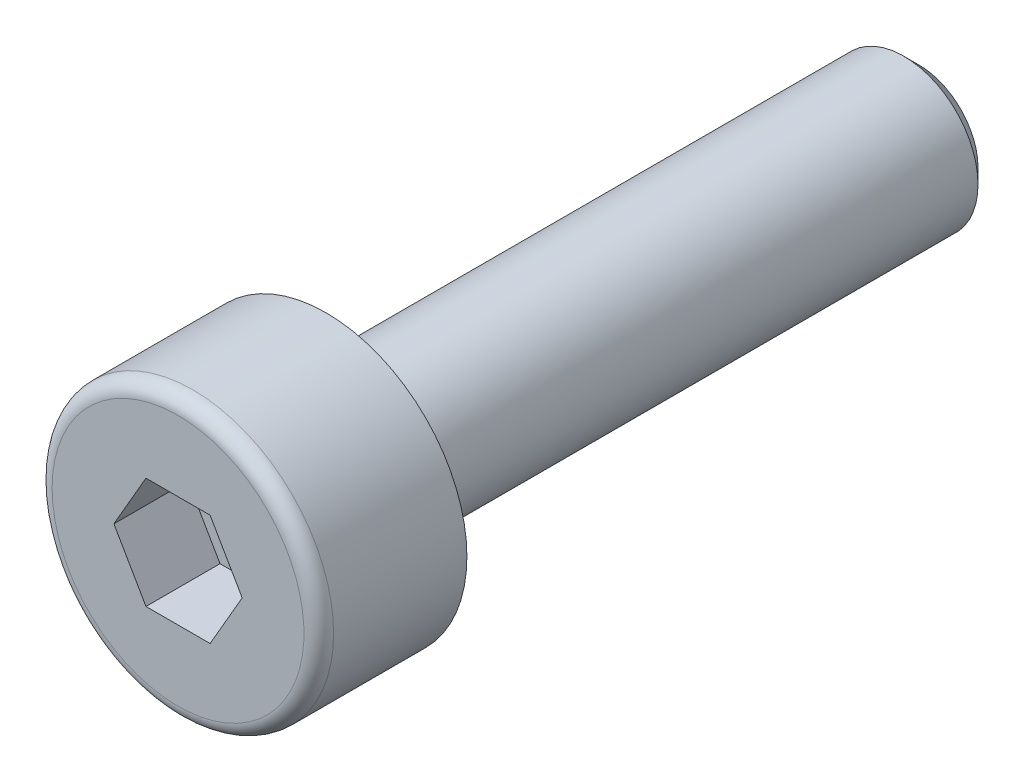
SolidWorks part; units mm, degrees
material "普通碳钢"
ref_plane "Front" through (0, 0, 0) normal (0, 0, 1) x (1, 0, 0)
ref_plane "Top" through (0, 0, 0) normal (0, 1, 0) x (1, 0, 0)
ref_plane "Right" through (0, 0, 0) normal (1, 0, 0) x (0, 0, -1)
sketch "Sketch2" plane through (0, 0, 0) normal (1, 0, 0) x (0, 0, -1)
  line L1 (0, 0) -> (0, 1.9)
  line L2 (0, 1.9) -> (2, 1.9)
  line L3 (2, 1.9) -> (2, 1)
  line L4 (2, 1) -> (10, 1)
  line L5 (10, 1) -> (10, 0)
  line L6 (0, 0) -> (10, 0)
  line L7 (0, 0) -> (0.7324, 0) construction
  dimension "头厚" = 2
  dimension "直径" = 2
  dimension "头径" = 3.8
revolve "Matrix-Rotate1" add sketch "Sketch2" angle 360 about L7
sketch "Sketch3" plane through (0, 0, 0) normal (0, 0, 1) x (1, 0, 0)
  line L1 (0.866, 0) -> (0.433, 0.75)
  line L2 (0.433, 0.75) -> (-0.433, 0.75)
  line L3 (-0.433, 0.75) -> (-0.866, 0)
  line L4 (-0.866, 0) -> (-0.433, -0.75)
  line L5 (-0.433, -0.75) -> (0.433, -0.75)
  line L6 (0.433, -0.75) -> (0.866, 0)
  circle A0 centre (0, 0) radius 0.75 construction
  dimension "槽宽" = 1.5
extrude "Extrude1" cut sketch "Sketch3" against normal blind 1
fillet "Fillet1" radius 0.2 1 edges at (1.9, 0, 0)
chamfer "倒角1" distance 0.2 angle 45 1 edges at (1, 0, -10)
equation "\"D1@倒角1\"=\"直径@Sketch2\"*0.1"
equation "\"D1@Fillet1\"=\"直径@Sketch2\"*0.1"
equation "\"t@Extrude1\"=\"直径@Sketch2\"/2"
